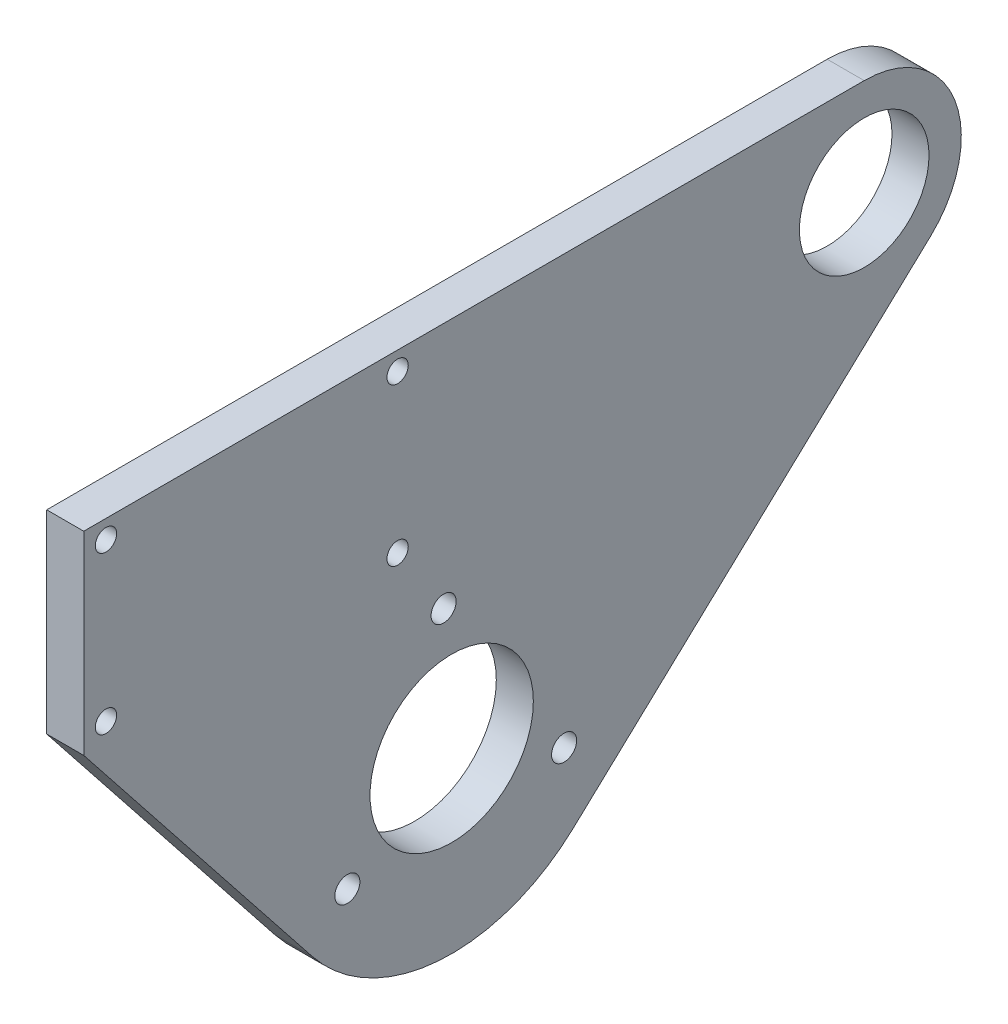
SolidWorks part; units mm, degrees
ref_plane "Front Plane" through (0, 0, 0) normal (0, 0, 1) x (1, 0, 0)
ref_plane "Top Plane" through (0, 0, 0) normal (0, 1, 0) x (1, 0, 0)
ref_plane "Right Plane" through (0, 0, 0) normal (1, 0, 0) x (0, 0, -1)
sketch "Sketch1" plane through (0, 0, 0) normal (1, 0, 0) x (0, 0, -1)
  line L0 (-49.9001, -69.4268) -> (11.3662, -12.16)
  line L1 (-133.81, 16.645) -> (-76.19, 16.645)
  line L2 (-133.81, 16.645) -> (-133.81, -16.645)
  line L3 (-133.81, -16.645) -> (-76.19, -16.645)
  line L4 (-76.19, 16.645) -> (-76.19, -16.645)
  line L5 (-130, 13.475) -> (-80, 13.475)
  line L6 (-130, 13.475) -> (-130, -13.475)
  line L7 (-130, -13.475) -> (-80, -13.475)
  line L8 (-80, 13.475) -> (-80, -13.475)
  line L9 (-76.19, 16.645) -> (0, 16.645)
  line L10 (-133.81, -16.645) -> (-94.6322, -66.0872)
  circle A0 centre (0, 0) radius 11.1125
  circle A1 centre (-70.7273, -47.145) radius 14
  circle A2 centre (-70.7273, -47.145) radius 21.5 construction
  circle A3 centre (-70.7273, -47.145) radius 30.5
  circle A4 centre (0, 0) radius 16.645
  point P4 (-133.81, 0)
  point P12 (-130, 0)
  dimension "D6" = 22.225
  dimension "D7" = 28
  dimension "D8" = 43
  dimension "D9" = 61
  dimension "D11" = 0
  dimension "D1" = 33.29
  dimension "D2" = 80
  dimension "D3" = 26.95
  dimension "D4" = 50
  dimension "D5" = 3.81
  dimension "D10" = 85
  dimension "D12" = 3.81
extrude "Boss-Extrude1" add sketch "Sketch1" along normal mid plane 6.35 contours A3 A1 | A4 L9 L4 L3 A3 L0 | A4 A0 | L4 L1 L2 L3 L5 L8 L7 L6 | L8 L5 L6 L7 | A3 L3 L10
hole_wizard "#6 Clearance Hole1" positions "Sketch2" profile "Sketch3" hole size "#6" standard "ANSI Inch" end condition up to next
sketch "Sketch2" plane through (3.175, 0, 0) normal (1, 0, 0) x (0, 0, -1)
  point P0 (-80, -13.475)
  point P3 (-80, 13.475)
  point P6 (-130, 13.475)
  point P9 (-130, -13.475)
sketch "Sketch3" plane through (3.175, -13.475, 80) normal (0, 1, 0) x (0, 0, -1)
  line L0 (0, 0) -> (0, 6.35)
  line L1 (0, 6.35) -> (1.8288, 6.35)
  line L2 (1.8288, 6.35) -> (1.8288, 0)
  line L5 (1.8288, 0) -> (0, 0)
  line L11 (0, -6.35) -> (0, 107.95) construction
  dimension "Thru Hole Dia." = 3.6576
  dimension "Thru Hole Depth" = 6.35
hole_wizard "M4 Clearance Hole1" positions "Sketch4" profile "Sketch5" hole size "M4" standard "ANSI Metric" end condition up to next
sketch "Sketch4" plane through (3.175, 0, 0) normal (1, 0, 0) x (0, 0, -1)
  line L0 (-69.5572, -46.365) -> (1.1701, 0.78) construction
  line L1 (-70.7273, -47.145) -> (-72.6883, -16.7081) construction
  line L3 (-70.7273, -47.145) -> (-43.3877, -60.6652) construction
  circle A0 centre (-70.7273, -47.145) radius 21.5 construction
  circle A1 centre (-70.7273, -47.145) radius 30.5 construction
  point P9 (-88.6171, -59.0699)
  point P26 (-51.4551, -56.6756)
  point P28 (-72.1096, -25.6895)
  dimension "D1" = 120
  dimension "D2" = 120
sketch "Sketch5" plane through (3.175, -25.6895, 72.1096) normal (0, 1, 0) x (0, 0, -1)
  line L0 (0, 0) -> (0, 6.35)
  line L1 (0, 6.35) -> (2.15, 6.35)
  line L2 (2.15, 6.35) -> (2.15, 0)
  line L5 (2.15, 0) -> (0, 0)
  line L11 (0, -6.35) -> (0, 107.95) construction
  dimension "Thru Hole Dia." = 4.3
  dimension "Thru Hole Depth" = 6.35
